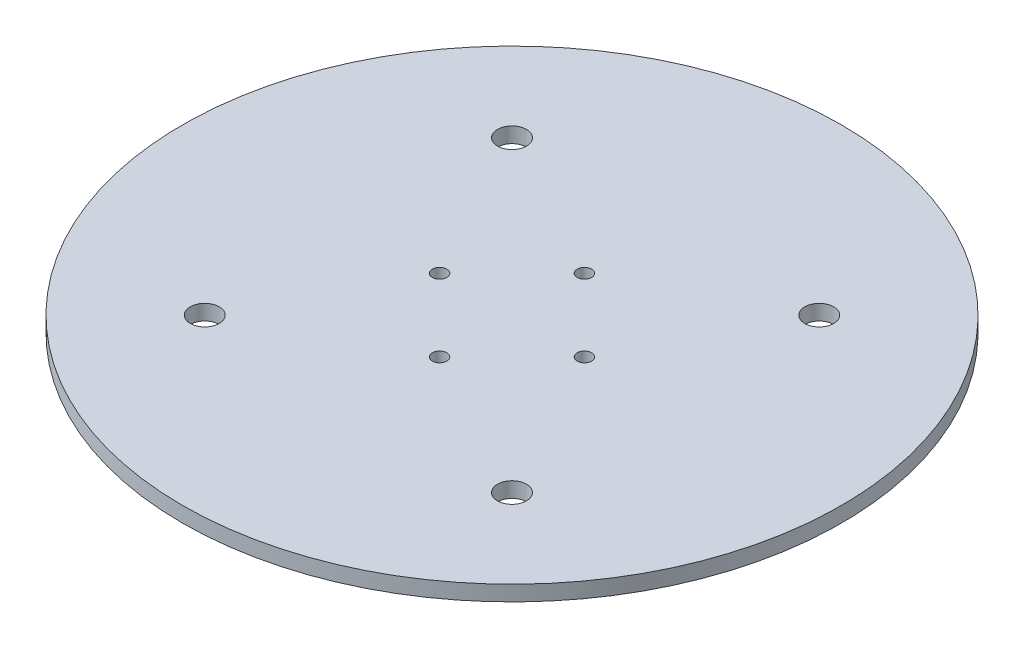
SolidWorks part; units mm, degrees
material "6063-O"
ref_plane "Front Plane" through (0, 0, 0) normal (0, 0, 1) x (1, 0, 0)
ref_plane "Top Plane" through (0, 0, 0) normal (0, 1, 0) x (1, 0, 0)
ref_plane "Right Plane" through (0, 0, 0) normal (1, 0, 0) x (0, 0, -1)
sketch "Sketch1" plane through (0, 0, 0) normal (0, 1, 0) x (1, 0, 0)
  circle A0 centre (0, 0) radius 34.1313
  dimension "D1" = 68.2625
extrude "Boss-Extrude1" add sketch "Sketch1" along normal blind 1.59
sketch "Sketch2" plane through (0, 1.59, 0) normal (0, 1, 0) x (1, 0, 0)
  circle A0 centre (0, 0) radius 7.5 construction
  circle A1 centre (0, -7.5) radius 0.75
  circle A2 centre (0, 7.5) radius 0.75
  circle A3 centre (-7.5, 0) radius 0.75
  circle A4 centre (7.5, 0) radius 0.75
  dimension "D1" = 15
  dimension "D2" = 1.5
extrude "Cut-Extrude1" cut sketch "Sketch2" against normal blind 1.59
sketch "Sketch3" plane through (0, 1.59, 0) normal (0, 1, 0) x (1, 0, 0)
  line L0 (0, 42.7049) -> (0, -43.2881) construction
  circle A0 centre (0, 0) radius 22.5 construction
  circle A1 centre (-15.909, 15.9108) radius 1.5
  circle A2 centre (0, 0) radius 22.5 construction
  circle A3 centre (15.9108, 15.909) radius 1.5
  circle A4 centre (0, 0) radius 22.5 construction
  circle A5 centre (15.909, -15.9108) radius 1.5
  circle A6 centre (0, 0) radius 22.5 construction
  circle A7 centre (-15.9108, -15.909) radius 1.5
  point P19 (0, 0)
  dimension "D1" = 45
  dimension "D2" = 3
  dimension "D3" = 15.909
  dimension "D4" = 4
extrude "Cut-Extrude2" cut sketch "Sketch3" against normal blind 1.59
